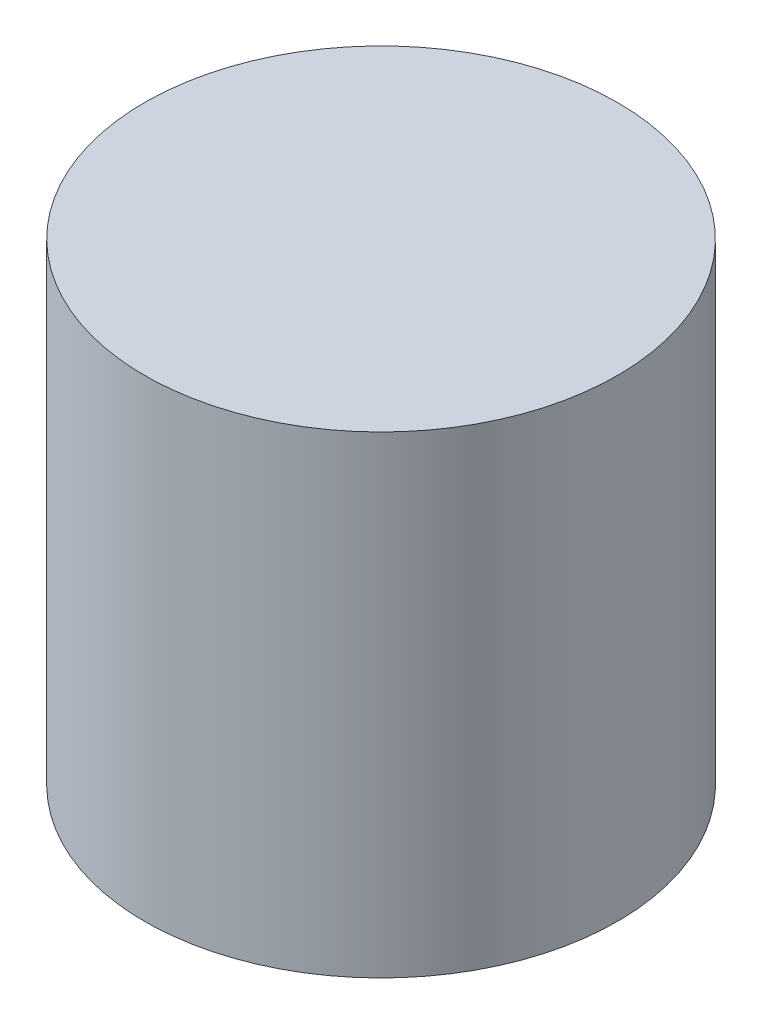
SolidWorks part; units mm, degrees
material "AISI 1020"
ref_plane "Front Plane" through (0, 0, 0) normal (0, 0, 1) x (1, 0, 0)
ref_plane "Top Plane" through (0, 0, 0) normal (0, 1, 0) x (1, 0, 0)
ref_plane "Right Plane" through (0, 0, 0) normal (1, 0, 0) x (0, 0, -1)
sketch "Sketch1" plane through (0, 0, 0) normal (1, 0, 0) x (0, 0, -1)
  line L0 (0, -3564.0143) -> (0, 174636.7017) construction
  line L1 (0, 158.549) -> (50, 158.549)
  line L2 (50, 158.549) -> (50, 108.549)
  line L5 (50, 58.549) -> (40, 58.549)
  line L6 (40, 58.549) -> (40, 138.549)
  line L7 (40, 138.549) -> (0, 138.549)
  line L8 (0, 138.549) -> (0, 158.549)
  line L9 (50, 108.549) -> (50, 58.549)
  point P5 (0, 0)
  dimension "D1" = 50
  dimension "D2" = 50
  dimension "D3" = 10
  dimension "D4" = 40
  dimension "D5" = 100
  dimension "D6" = 80
revolve "Revolve1" add sketch "Sketch1" angle 360 about L0
